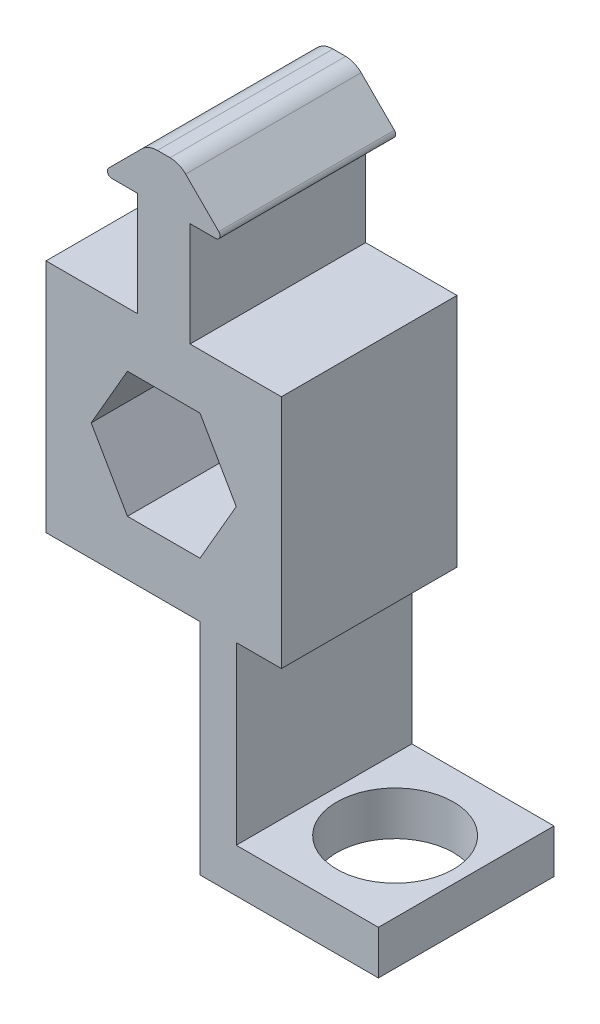
SolidWorks part; units mm, degrees
ref_plane "Front Plane" through (0, 0, 0) normal (0, 0, 1) x (1, 0, 0)
ref_plane "Top Plane" through (0, 0, 0) normal (0, 1, 0) x (1, 0, 0)
ref_plane "Right Plane" through (0, 0, 0) normal (1, 0, 0) x (0, 0, -1)
sketch "Sketch1" plane through (0, 0, 0) normal (0, 0, 1) x (1, 0, 0)
  line L0 (-13.6207, 13.6208) -> (-13.6207, -13.6207)
  line L1 (-4.1978, 7.2708) -> (-8.3955, 0)
  line L2 (-8.3955, 0) -> (-4.1978, -7.2707)
  line L3 (-4.1978, -7.2707) -> (4.1978, -7.2707)
  line L4 (4.1978, -7.2707) -> (8.3955, 0)
  line L5 (8.3955, 0) -> (4.1978, 7.2708)
  line L6 (4.1978, 7.2708) -> (-4.1978, 7.2708)
  line L7 (-13.6207, -13.6207) -> (13.6208, -13.6207)
  line L8 (13.6208, -13.6207) -> (13.6208, 13.6208)
  line L9 (-13.6207, 13.6208) -> (-3.048, 13.6208)
  line L10 (-3.048, 13.6208) -> (-3.048, 25.6857)
  line L11 (-3.048, 25.6857) -> (-6.0126, 25.6857)
  line L12 (-6.3718, 26.553) -> (-2.5321, 30.3926)
  line L13 (-0.7361, 31.1366) -> (0.7361, 31.1366)
  line L14 (0, 41.8096) -> (0, -25.778) construction
  line L15 (13.6208, 13.6208) -> (3.048, 13.6207)
  line L16 (3.048, 13.6207) -> (3.048, 25.6857)
  line L17 (6.3718, 26.553) -> (2.5321, 30.3926)
  line L18 (3.048, 25.6857) -> (6.0126, 25.6857)
  circle A0 centre (0, 0) radius 7.2707 construction
  arc A1 (-6.0126, 25.6857) -> (-6.3718, 26.553) centre (-6.0126, 26.1938) cw
  arc A2 (-2.5321, 30.3926) -> (-0.7361, 31.1366) centre (-0.7361, 28.5966) cw
  arc A3 (2.5321, 30.3926) -> (0.7361, 31.1366) centre (0.7361, 28.5966) ccw
  arc A4 (6.0126, 25.6857) -> (6.3718, 26.553) centre (6.0126, 26.1938) ccw
  point P18 (7.239, 25.6857)
  point P21 (-4.5303, 25.6857)
  point P25 (-7.239, 25.6857)
  point P29 (0, -13.6208)
  point P35 (0, 31.1366)
  dimension "D7" = 0.508
  dimension "D8" = 2.54
  dimension "D1" = 14.5415
  dimension "D2" = 18.415
  dimension "D3" = 6.096
  dimension "D4" = 5.4508
  dimension "D5" = 135
  dimension "D6" = 14.478
  dimension "D9" = 6.35
  dimension "D10" = 6.35
extrude "Boss-Extrude1" add sketch "Sketch1" along normal mid plane 20.32
sketch "Hole Placement for Solenoid" plane through (13.6208, 0, 0) normal (1, 0, 0) x (0, 0, -1)
  line L0 (0, 33.0147) -> (0, -17.9195) construction
  line L1 (-10.16, -13.6208) -> (10.16, -13.6208) construction
  point P3 (2.825, 1.3793)
  point P4 (-3.175, -8.6207)
  dimension "D1" = 5
  dimension "D2" = 10
  dimension "D3" = 6
  dimension "D4" = 3.175
sketch "Sketch3" plane through (0, -13.6207, 0) normal (0, -1, 0) x (1, 0, 0)
  line L0 (8.3955, 10.16) -> (8.3955, -10.16) construction
  line L3 (8.3955, 10.16) -> (8.3955, -10.16)
  line L7 (4.1978, 10.16) -> (4.1978, -10.16) construction
  line L8 (4.1978, 10.16) -> (4.1978, -10.16)
  line L9 (4.1978, 10.16) -> (8.3955, 10.16)
  line L10 (4.1978, -10.16) -> (8.3955, -10.16)
extrude "Boss-Extrude2" add sketch "Sketch3" along normal blind 25.4
sketch "Sketch4" plane through (0, -39.0207, 0) normal (0, -1, 0) x (1, 0, 0)
  line L2 (8.3955, 10.16) -> (24.846, 10.16)
  line L3 (24.846, 10.16) -> (24.846, -10.16)
  line L4 (24.846, -10.16) -> (8.3955, -10.16)
  line L8 (8.3955, -10.16) -> (8.3955, 10.16) construction
  line L9 (8.3955, -10.16) -> (8.3955, 10.16)
  line L10 (13.6208, 10.16) -> (13.6208, -10.16) construction
  line L11 (13.6208, 10.16) -> (13.6208, -10.16) construction
  circle A0 centre (16.6208, 0) radius 6.75
  point P1 (0, 0)
  point P6 (0, 0)
  point P7 (16.6208, 10.16)
  point P8 (0, 0)
  point P12 (0, 0)
  point P13 (0, 0)
  dimension "D1" = 13.5
  dimension "D2" = 3
extrude "Boss-Extrude3" add sketch "Sketch4" against normal blind 5.08
